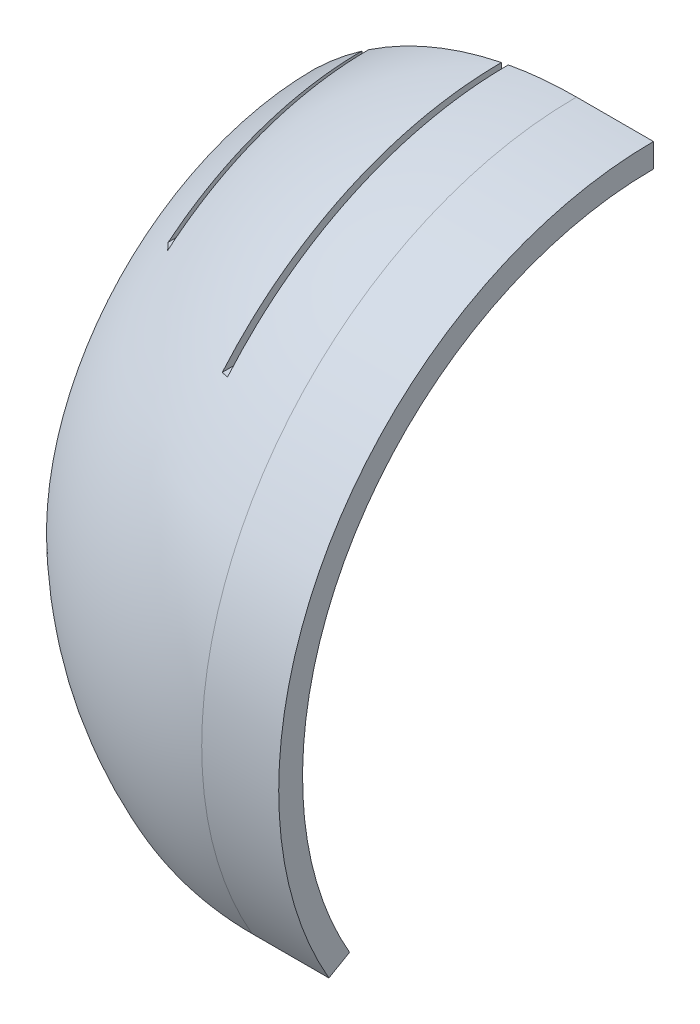
SolidWorks part; units mm, degrees
material "铸造合金钢"
ref_plane "前视基准面" through (0, 0, 0) normal (0, 0, 1) x (1, 0, 0)
ref_plane "上视基准面" through (0, 0, 0) normal (0, 1, 0) x (1, 0, 0)
ref_plane "右视基准面" through (0, 0, 0) normal (1, 0, 0) x (0, 0, -1)
sketch "草图1" plane through (0, 0, 0) normal (0, 0, 1) x (1, 0, 0)
  line L0 (0, 0) -> (0, 31.2525) construction
  line L1 (0, 55) -> (0, 51.5)
  line L2 (0, -51.5) -> (0, -55)
  arc A0 (0, 55) -> (0, -55) centre (0, 0) ccw
  arc A1 (0, 51.5) -> (0, -51.5) centre (0, 0) ccw
  dimension "D1" = 110
  dimension "D2" = 103
revolve "旋转8" add sketch "草图1" angle 360 about L0
sketch "草图2" plane through (0, 0, 0) normal (0, 0, 1) x (1, 0, 0)
  line L0 (0, 55) -> (0, -55)
  line L1 (0, -55) -> (55, -55)
  line L2 (55, -55) -> (55, 55)
  line L3 (55, 55) -> (0, 55)
  circle A0 centre (0, 0) radius 55 construction
extrude "切除-拉伸1" cut sketch "草图2" against normal through all both and the other way through all
sketch "草图3" plane through (0, 0, 0) normal (0, 0, 1) x (1, 0, 0)
  line L0 (0, 55) -> (-38.5, 55)
  line L1 (-38.5, 55) -> (-38.5, -55)
  line L2 (-38.5, -55) -> (0, -55)
  line L3 (0, -55) -> (0, 55) construction
  line L4 (-38.5, 55) -> (-61.7731, 55)
  line L5 (-61.7731, 55) -> (-61.7731, -55)
  line L6 (-61.7731, -55) -> (-38.5, -55)
  arc A0 (0, 55) -> (0, -55) centre (0, 0) ccw construction
  dimension "D1" = 38.5
extrude "切除-拉伸2" cut sketch "草图3" against normal through all both and the other way through all contours L5 L6 L1 L4
sketch "草图4" plane through (-38.5, 0, 0) normal (-1, 0, 0) x (0, 0, 1)
  line L0 (0, 0) -> (0, 64.5299)
  line L1 (0, 0) -> (55.8845, -32.2649)
  arc A0 (0, 64.5299) -> (55.8845, -32.2649) centre (0, 0) ccw
  dimension "D1" = 120
extrude "切除-拉伸3" cut sketch "草图4" against normal through all
sketch "草图5" plane through (0, 0, 0) normal (0, 0, -1) x (-1, 0, 0)
  line L0 (30.5, 55) -> (30.5, 35)
  line L1 (30.5, 55) -> (31.5, 55)
  line L2 (31.5, 55) -> (31.5, 35)
  line L3 (31.5, 35) -> (30.5, 35)
  line L4 (38.5, -17.1026) -> (38.5, 34.2053) construction
  line L5 (0, 55) -> (49.1042, 55) construction
  line L6 (0, 51.5) -> (0, -25.75) construction
  line L8 (10, 35) -> (10, 55)
  line L9 (10, 55) -> (11, 55)
  line L10 (11, 55) -> (11, 35)
  line L11 (11, 35) -> (10, 35)
  dimension "D1" = 8
  dimension "D2" = 1
  dimension "D3" = 20
  dimension "D4" = 11
  dimension "D5" = 1
extrude "切除-拉伸4" cut sketch "草图5" against normal through all
sketch "草图6" plane through (0, 0, 0) normal (0, 0, 1) x (1, 0, 0)
  line L0 (0, 55) -> (11.3, 55)
  line L1 (11.3, 55) -> (11.3, 51.5)
  line L2 (11.3, 51.5) -> (0, 51.5)
  line L3 (0, -27.5) -> (0, 55) construction
  line L4 (0, 51.5) -> (0, 55)
  line L5 (0, 0) -> (14.7554, 0) construction
  dimension "D1" = 3.5
  dimension "D2" = 11.3
revolve "旋转9" add sketch "草图6" angle 360 about L5
sketch "草图7" plane through (0, 0, 0) normal (-1, 0, 0) x (0, 0, 1)
  line L0 (0, 55) -> (0, 0)
  line L1 (0, 0) -> (47.6314, -27.5)
  arc A0 (0, 55) -> (47.6314, -27.5) centre (0, 0) ccw
extrude "切除-拉伸5" cut sketch "草图7" against normal blind 10
sketch "草图8" plane through (10, 0, 0) normal (-1, 0, 0) x (0, 0, 1)
  line L0 (0, 55) -> (0, 0)
  line L1 (0, 0) -> (47.6314, -27.5)
  arc A0 (0, 55) -> (47.6314, -27.5) centre (0, 0) ccw
extrude "切除-拉伸6" cut sketch "草图8" against normal blind 10
